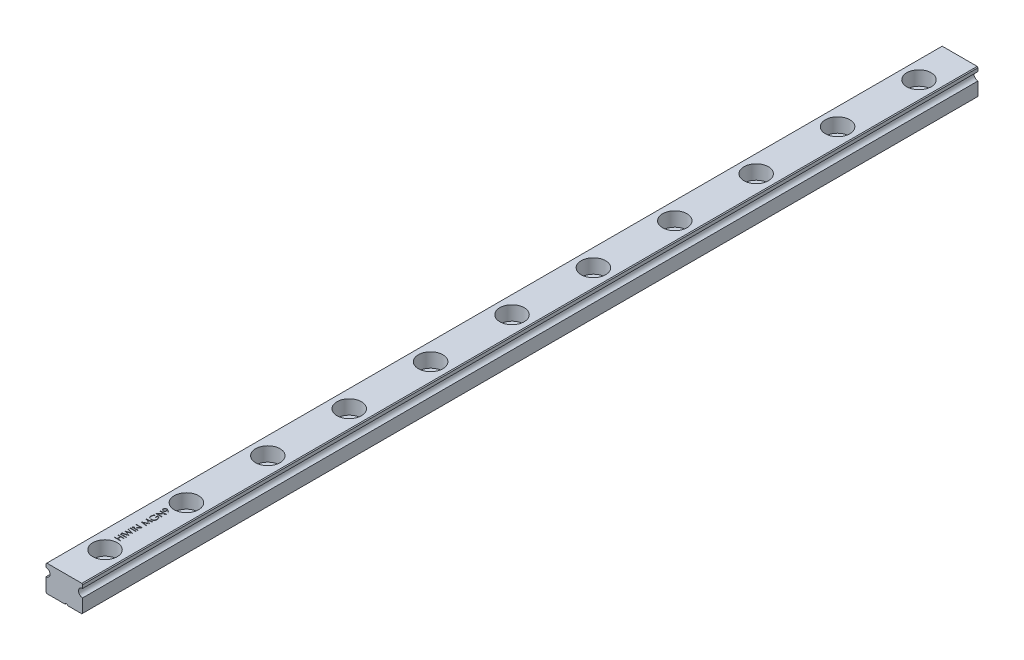
SolidWorks part; units mm, degrees
material "镀铬不锈钢"
ref_plane "前视基准面" through (0, 0, 0) normal (0, 0, 1) x (1, 0, 0)
ref_plane "上视基准面" through (0, 0, 0) normal (0, 1, 0) x (1, 0, 0)
ref_plane "右视基准面" through (0, 0, 0) normal (1, 0, 0) x (0, 0, -1)
sketch "草图1" plane through (0, 0, 0) normal (0, 0, 1) x (1, 0, 0)
  line L2 (4.5, 5.5) -> (4.5, 6.3)
  line L3 (-4.3, 6.5) -> (-4.5, 6.3)
  line L4 (4.5, 0.2) -> (4.5, 3.5)
  line L5 (4.3, 6.5) -> (-4.3, 6.5)
  line L6 (4.5, 6.3) -> (4.3, 6.5)
  line L7 (-4.3, 0) -> (0.2, 0)
  line L8 (4.3, 0) -> (4.5, 0.2)
  line L9 (0.8, 0) -> (4.3, 0)
  line L10 (-4.5, 0.2) -> (-4.3, 0)
  line L11 (0, 6.5) -> (0, 0) construction
  line L12 (-4.5, 3.5) -> (-4.5, 0.2)
  line L13 (-4.5, 6.3) -> (-4.5, 5.5)
  arc A0 (-4.5, 3.5) -> (-4.5, 5.5) centre (-4.5, 4.5) ccw
  arc A1 (0.8, 0) -> (0.2, 0) centre (0.5, 0) ccw
  arc A2 (4.5, 5.5) -> (4.5, 3.5) centre (4.5, 4.5) ccw
extrude "凸台-拉伸1" add sketch "草图1" against normal blind 220
hole_wizard "M3 六角凹头螺钉的柱形沉头孔1" positions "草图3" profile "草图2" counterbore size "M3" standard "ISO" end condition through all
sketch "草图3" plane through (0.7549, 6.5, 19.3435) normal (0, 1, 0) x (-1, 0, 0)
  point P0 (0.7549, -29.3435)
  dimension "D1" = 10
sketch "草图2" plane through (0, 6.5, -10) normal (1, 0, 0) x (0, 0, 1)
  line L0 (0, 0) -> (0, 6.5)
  line L1 (0, 6.5) -> (1.75, 6.5)
  line L3 (1.75, 6.5) -> (1.75, 3.5)
  line L4 (1.75, 3.5) -> (3, 3.5)
  line L5 (3, 3.5) -> (3, 0)
  line L7 (3, 0) -> (0, 0)
  line L11 (0, -6.35) -> (0, 107.95) construction
  dimension "通孔孔直径" = 3.5
  dimension "通孔孔深度" = 6.5
  dimension "柱形沉头孔直径" = 6
  dimension "柱形沉头孔深度" = 3.5
pattern_linear "阵列(线性)1" count 11 spacing 20 along (0, 0, -1) of "M3 六角凹头螺钉的柱形沉头孔1"
sketch "草图6" plane through (0, 6.5, 0) normal (0, 1, 0) x (1, 0, 0)
  line L0 (0, 10) -> (0, 30) construction
  text T0 "HIWIN MGN9" font "Century Gothic" height 1.5
extrude "切除-拉伸1" cut sketch "草图6" against normal blind 0.1
